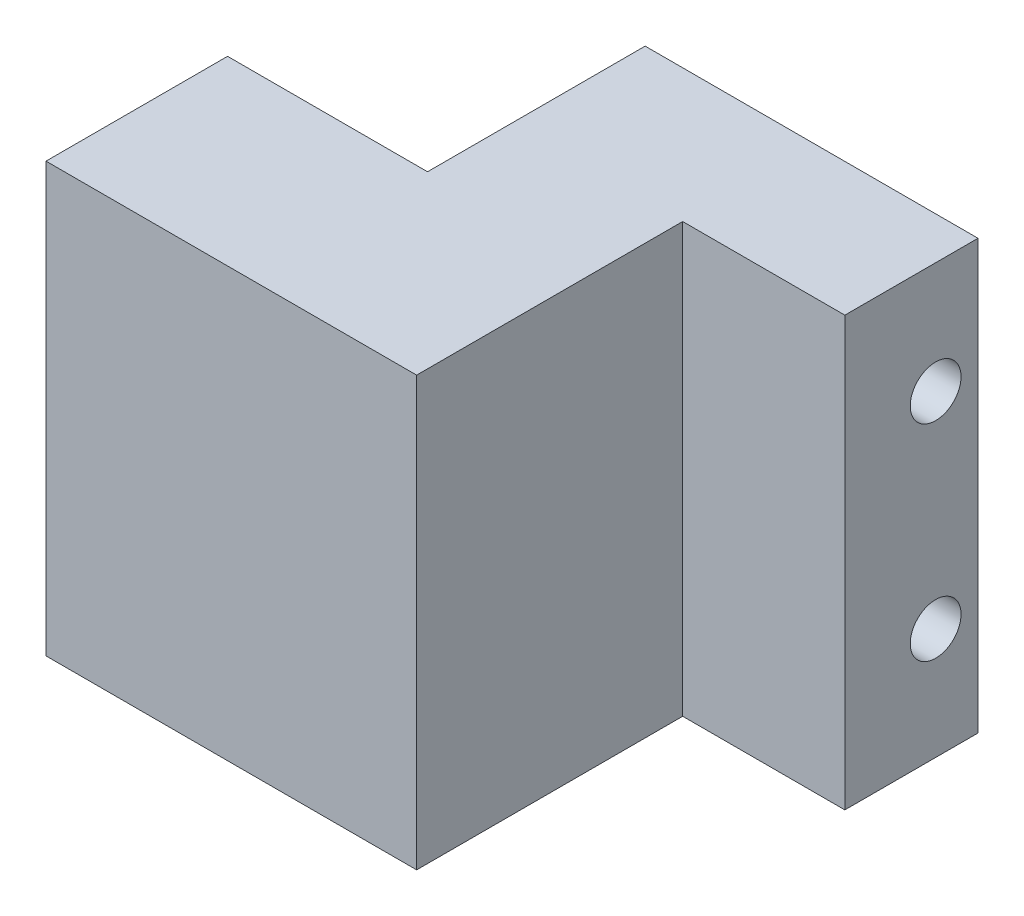
SolidWorks part; units mm, degrees
ref_plane "Front Plane" through (0, 0, 0) normal (0, 0, 1) x (1, 0, 0)
ref_plane "Top Plane" through (0, 0, 0) normal (0, 1, 0) x (1, 0, 0)
ref_plane "Right Plane" through (0, 0, 0) normal (1, 0, 0) x (0, 0, -1)
sketch "Sketch1" plane through (0, 0, 0) normal (0, 1, 0) x (1, 0, 0)
  line L0 (1.0174, 2.98) -> (-26.48, 2.98)
  line L22 (-11.48, -8.02) -> (1.0174, -8.02)
  line L25 (-31.48, -15) -> (-43, -15)
  line L27 (-11.48, -8.02) -> (-12.38, -8.02)
  line L29 (-31.48, -15) -> (-26.48, -15)
  line L31 (-26.48, 2.98) -> (-26.48, -15)
  line L32 (-43, -15) -> (-43, -30)
  line L33 (-43, -30) -> (-12.38, -30)
  line L34 (-12.38, -30) -> (-12.38, -8.02)
  line L35 (1.0174, 2.98) -> (1.0174, -8.02)
  dimension "D1" = 0.9
  dimension "D2" = 5
extrude "Boss-Extrude1" add sketch "Sketch1" along normal blind 35.4
sketch "Sketch2" plane through (-43, 0, 0) normal (-1, 0, 0) x (0, 0, 1)
  line L1 (26.815, 4.925) -> (18.185, 4.925)
  line L2 (26.815, 4.925) -> (26.815, 30.475)
  line L3 (26.815, 30.475) -> (18.185, 30.475)
  line L4 (18.185, 4.925) -> (18.185, 30.475)
  line L5 (26.815, 4.925) -> (18.185, 30.475) construction
  line L6 (26.815, 30.475) -> (18.185, 4.925) construction
  point P2 (0, 0)
  point P4 (25, 17.7)
  dimension "D1" = 25.55
  dimension "D2" = 8.63
extrude "Cut-Extrude1" cut sketch "Sketch2" against normal blind 30
sketch "Sketch3" plane through (1.0174, 0, 0) normal (1, 0, 0) x (0, 0, -1)
  circle A2 centre (-0.52, 9.2) radius 2.1
  circle A3 centre (-0.52, 26.2) radius 2.1
  point P5 (0.48, 17.7)
  point P14 (0.48, 17.7)
  dimension "D2" = 4.2
extrude "Cut-Extrude2" cut sketch "Sketch3" against normal through all
sketch "Sketch4" plane through (-26.48, 0, 0) normal (-1, 0, 0) x (0, 0, 1)
  line L7 (-4.5943, 9.2) -> (-2.0372, 4.7709)
  line L8 (-2.0372, 4.7709) -> (3.0772, 4.7709)
  line L9 (3.0772, 4.7709) -> (5.6343, 9.2)
  line L10 (5.6343, 9.2) -> (3.0772, 13.6291)
  line L11 (3.0772, 13.6291) -> (-2.0372, 13.6291)
  line L12 (-2.0372, 13.6291) -> (-4.5943, 9.2)
  line L13 (-4.5943, 26.2) -> (-2.0372, 21.7709)
  line L14 (-2.0372, 21.7709) -> (3.0772, 21.7709)
  line L15 (3.0772, 21.7709) -> (5.6343, 26.2)
  line L16 (5.6343, 26.2) -> (3.0772, 30.6291)
  line L17 (3.0772, 30.6291) -> (-2.0372, 30.6291)
  line L18 (-2.0372, 30.6291) -> (-4.5943, 26.2)
  circle A0 centre (0.52, 26.2) radius 4.4291 construction
  circle A1 centre (0.52, 9.2) radius 4.4291 construction
extrude "Cut-Extrude3" cut sketch "Sketch4" against normal blind 4.7625
